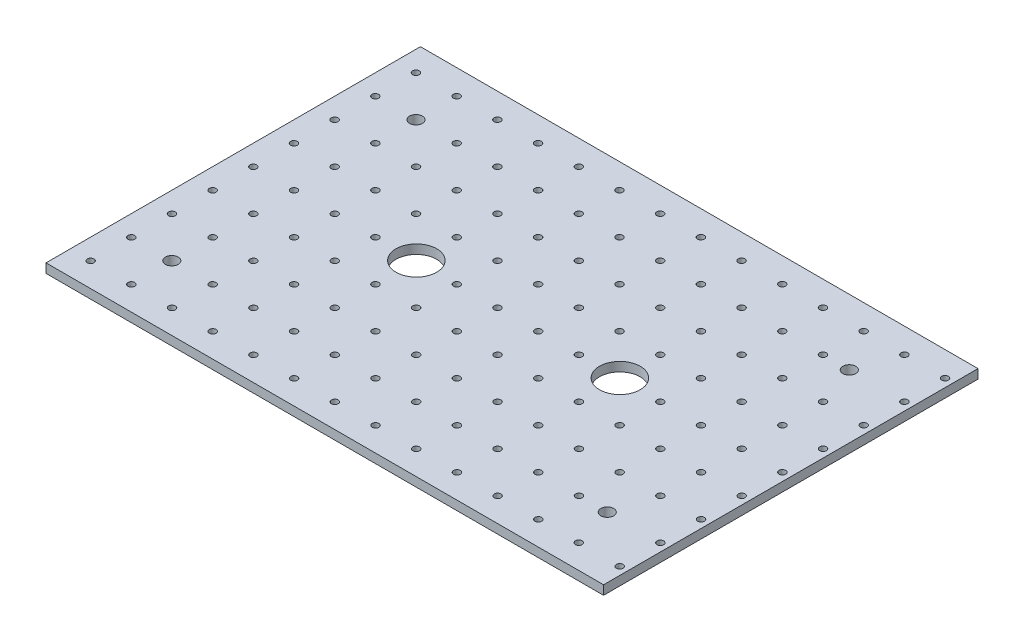
SolidWorks part; units mm, degrees
ref_plane "Front Plane" through (0, 0, 0) normal (0, 0, 1) x (1, 0, 0)
ref_plane "Top Plane" through (0, 0, 0) normal (0, 1, 0) x (1, 0, 0)
ref_plane "Right Plane" through (0, 0, 0) normal (1, 0, 0) x (0, 0, -1)
sketch "Sketch2" plane through (0, 0, 0) normal (0, 1, 0) x (1, 0, 0)
  line L0 (137.1216, 89.8078) -> (-136.8784, 89.8078) construction
  line L1 (-137, 92) -> (137, 92)
  line L2 (-137, 92) -> (-137, -92)
  line L3 (-137, -92) -> (137, -92)
  line L4 (137, 92) -> (137, -92)
  line L5 (-137, 92) -> (137, -92) construction
  line L6 (-137, -92) -> (137, 92) construction
  line L8 (137.1216, -90.1922) -> (-136.8784, -90.1922) construction
  circle A0 centre (-127, 79.8078) radius 1.65
  circle A2 centre (-87, 79.8078) radius 1.65
  circle A3 centre (-67, 79.8078) radius 1.65
  circle A4 centre (-47, 79.8078) radius 1.65
  circle A5 centre (-27, 79.8078) radius 1.65
  circle A6 centre (-7, 79.8078) radius 1.65
  circle A7 centre (13, 79.8078) radius 1.65
  circle A8 centre (33, 79.8078) radius 1.65
  circle A9 centre (53, 79.8078) radius 1.65
  circle A10 centre (73, 79.8078) radius 1.65
  circle A11 centre (93, 79.8078) radius 1.65
  circle A13 centre (133, 79.8078) radius 1.65
  circle A15 centre (-86.9848, 59.8078) radius 1.65
  circle A16 centre (-66.9848, 59.8078) radius 1.65
  circle A17 centre (-46.9848, 59.8078) radius 1.65
  circle A18 centre (-26.9848, 59.8078) radius 1.65
  circle A19 centre (-6.9848, 59.8078) radius 1.65
  circle A20 centre (13.0152, 59.8078) radius 1.65
  circle A21 centre (33.0152, 59.8078) radius 1.65
  circle A22 centre (53.0152, 59.8078) radius 1.65
  circle A23 centre (73.0152, 59.8078) radius 1.65
  circle A24 centre (93.0152, 59.8078) radius 1.65
  circle A26 centre (133.0152, 59.8078) radius 1.65
  circle A27 centre (-106.9696, 39.8078) radius 1.65
  circle A28 centre (-86.9696, 39.8078) radius 1.65
  circle A29 centre (-66.9696, 39.8078) radius 1.65
  circle A30 centre (-46.9696, 39.8078) radius 1.65
  circle A31 centre (-26.9696, 39.8078) radius 1.65
  circle A32 centre (-6.9696, 39.8078) radius 1.65
  circle A33 centre (13.0304, 39.8078) radius 1.65
  circle A34 centre (33.0304, 39.8078) radius 1.65
  circle A35 centre (53.0304, 39.8078) radius 1.65
  circle A36 centre (73.0304, 39.8078) radius 1.65
  circle A37 centre (93.0304, 39.8078) radius 1.65
  circle A38 centre (113.0304, 39.8078) radius 1.65
  circle A39 centre (133.0304, 39.8078) radius 1.65
  circle A40 centre (-106.9544, 19.8078) radius 1.65
  circle A41 centre (-86.9544, 19.8078) radius 1.65
  circle A42 centre (-66.9544, 19.8078) radius 1.65
  circle A43 centre (-46.9544, 19.8078) radius 1.65
  circle A44 centre (-26.9544, 19.8078) radius 1.65
  circle A45 centre (-6.9544, 19.8078) radius 1.65
  circle A46 centre (13.0456, 19.8078) radius 1.65
  circle A47 centre (33.0456, 19.8078) radius 1.65
  circle A48 centre (53.0456, 19.8078) radius 1.65
  circle A49 centre (73.0456, 19.8078) radius 1.65
  circle A50 centre (93.0456, 19.8078) radius 1.65
  circle A51 centre (113.0456, 19.8078) radius 1.65
  circle A52 centre (133.0456, 19.8078) radius 1.65
  circle A53 centre (-106.9392, -0.1922) radius 1.65
  circle A54 centre (-86.9392, -0.1922) radius 1.65
  circle A55 centre (-66.9392, -0.1922) radius 1.65
  circle A57 centre (-26.9392, -0.1922) radius 1.65
  circle A58 centre (-6.9392, -0.1922) radius 1.65
  circle A59 centre (13.0608, -0.1922) radius 1.65
  circle A60 centre (33.0608, -0.1922) radius 1.65
  circle A62 centre (73.0608, -0.1922) radius 1.65
  circle A63 centre (93.0608, -0.1922) radius 1.65
  circle A64 centre (113.0608, -0.1922) radius 1.65
  circle A65 centre (133.0608, -0.1922) radius 1.65
  circle A66 centre (-106.924, -20.1922) radius 1.65
  circle A67 centre (-86.924, -20.1922) radius 1.65
  circle A68 centre (-66.924, -20.1922) radius 1.65
  circle A69 centre (-46.924, -20.1922) radius 1.65
  circle A70 centre (-26.924, -20.1922) radius 1.65
  circle A71 centre (-6.924, -20.1922) radius 1.65
  circle A72 centre (13.076, -20.1922) radius 1.65
  circle A73 centre (33.076, -20.1922) radius 1.65
  circle A74 centre (53.076, -20.1922) radius 1.65
  circle A75 centre (73.076, -20.1922) radius 1.65
  circle A76 centre (93.076, -20.1922) radius 1.65
  circle A77 centre (113.076, -20.1922) radius 1.65
  circle A78 centre (133.076, -20.1922) radius 1.65
  circle A79 centre (-106.9088, -40.1922) radius 1.65
  circle A80 centre (-86.9088, -40.1922) radius 1.65
  circle A81 centre (-66.9088, -40.1922) radius 1.65
  circle A82 centre (-46.9088, -40.1922) radius 1.65
  circle A83 centre (-26.9088, -40.1922) radius 1.65
  circle A84 centre (-6.9088, -40.1922) radius 1.65
  circle A85 centre (13.0912, -40.1922) radius 1.65
  circle A86 centre (33.0912, -40.1922) radius 1.65
  circle A87 centre (53.0912, -40.1922) radius 1.65
  circle A88 centre (73.0912, -40.1922) radius 1.65
  circle A89 centre (93.0912, -40.1922) radius 1.65
  circle A90 centre (113.0912, -40.1922) radius 1.65
  circle A91 centre (133.0912, -40.1922) radius 1.65
  circle A93 centre (-86.8936, -60.1922) radius 1.65
  circle A94 centre (-66.8936, -60.1922) radius 1.65
  circle A95 centre (-46.8936, -60.1922) radius 1.65
  circle A96 centre (-26.8936, -60.1922) radius 1.65
  circle A97 centre (-6.8936, -60.1922) radius 1.65
  circle A98 centre (13.1064, -60.1922) radius 1.65
  circle A99 centre (33.1064, -60.1922) radius 1.65
  circle A100 centre (53.1064, -60.1922) radius 1.65
  circle A101 centre (73.1064, -60.1922) radius 1.65
  circle A102 centre (93.1064, -60.1922) radius 1.65
  circle A104 centre (133.1064, -60.1922) radius 1.65
  circle A106 centre (-86.8784, -80.1922) radius 1.65
  circle A107 centre (-66.8784, -80.1922) radius 1.65
  circle A108 centre (-46.8784, -80.1922) radius 1.65
  circle A109 centre (-26.8784, -80.1922) radius 1.65
  circle A110 centre (-6.8784, -80.1922) radius 1.65
  circle A111 centre (13.1216, -80.1922) radius 1.65
  circle A112 centre (33.1216, -80.1922) radius 1.65
  circle A113 centre (53.1216, -80.1922) radius 1.65
  circle A114 centre (73.1216, -80.1922) radius 1.65
  circle A115 centre (93.1216, -80.1922) radius 1.65
  circle A117 centre (133.1216, -80.1922) radius 1.65
  circle A118 centre (-126.9848, 59.8078) radius 1.65
  circle A119 centre (-126.9696, 39.8078) radius 1.65
  circle A120 centre (-126.9544, 19.8078) radius 1.65
  circle A121 centre (-126.9392, -0.1922) radius 1.65
  circle A122 centre (-126.924, -20.1922) radius 1.65
  circle A123 centre (-126.9088, -40.1922) radius 1.65
  circle A124 centre (-126.8936, -60.1922) radius 1.65
  circle A125 centre (-126.8784, -80.1922) radius 1.65
  circle A126 centre (-107, 59.8078) radius 3.15
  circle A127 centre (-107, 79.8078) radius 1.65 [skipped]
  circle A128 centre (-107, -60.1922) radius 3.15
  circle A129 centre (-106.8784, -80.1922) radius 1.65 [skipped]
  circle A130 centre (107, -60.1922) radius 3.15
  circle A131 centre (113.1216, -80.1922) radius 1.65 [skipped]
  circle A132 centre (105.9382, 59.8078) radius 3.15
  circle A133 centre (113, 79.8078) radius 1.65 [skipped]
  circle A134 centre (53, 0) radius 10
  circle A135 centre (53.0608, -0.1922) radius 1.65 [skipped]
  circle A136 centre (-47, 0) radius 10
  circle A137 centre (-46.9392, -0.1922) radius 1.65 [skipped]
  circle A138 centre (113.1064, -60.1922) radius 1.65 [skipped]
  circle A139 centre (113, -80.1922) radius 1.65
  circle A140 centre (113.0152, 59.8078) radius 1.65 [skipped]
  circle A141 centre (113, 79.8078) radius 1.65
  circle A142 centre (-106.8936, -60.1922) radius 1.65 [skipped]
  circle A143 centre (-106.8784, -80.1922) radius 1.65
  circle A144 centre (-106.9848, 59.8078) radius 1.65 [skipped]
  circle A145 centre (-107, 79.8078) radius 1.65
  point P0 (0, 0)
  dimension "D5" = 3.3
  dimension "D8" = 6.3
  dimension "D10" = 30
  dimension "D13" = 6.3
  dimension "D16" = 6.3
  dimension "D17" = 6.3
  dimension "D19" = 20
  dimension "D20" = 20
  dimension "D1" = 274
  dimension "D2" = 184
  dimension "D3" = 10
  dimension "D4" = 10
  dimension "D9" = 30
  dimension "D11" = 30
  dimension "D12" = 30
  dimension "D14" = 30
  dimension "D15" = 30
  dimension "D18" = 30
  dimension "D21" = 20
  dimension "D22" = 20
  dimension "D23" = 20
  dimension "D6" = 14
  dimension "D7" = 9
extrude "Boss-Extrude1" add sketch "Sketch2" along normal mid plane 4.5
